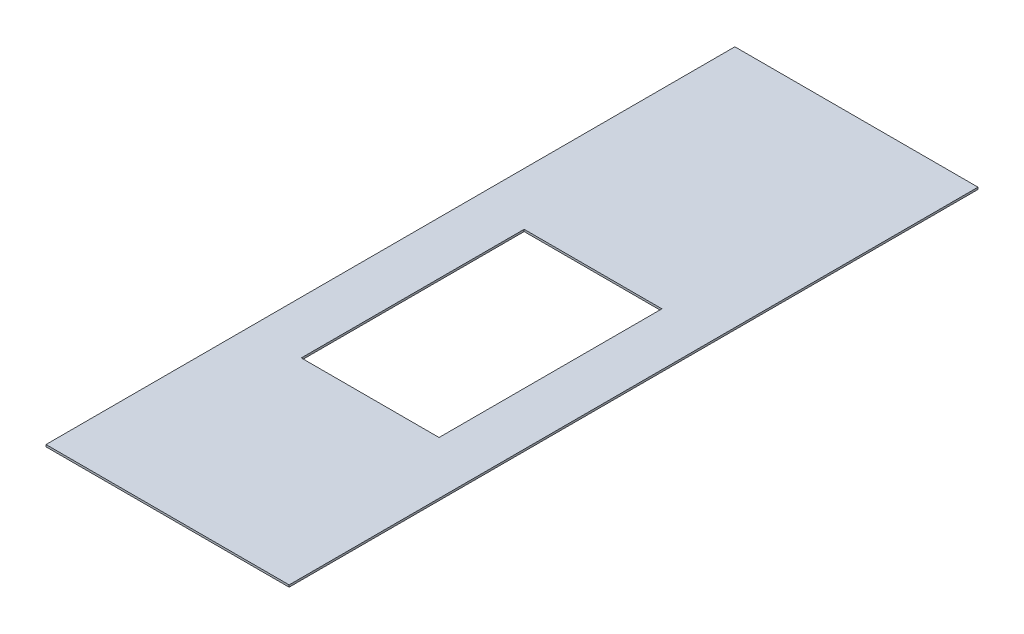
SolidWorks part; units mm, degrees
ref_plane "Front Plane" through (0, 0, 0) normal (0, 0, 1) x (1, 0, 0)
ref_plane "Top Plane" through (0, 0, 0) normal (0, 1, 0) x (1, 0, 0)
ref_plane "Right Plane" through (0, 0, 0) normal (1, 0, 0) x (0, 0, -1)
sketch "Sketch1" plane through (0, 0, 0) normal (0, 1, 0) x (1, 0, 0)
  line L1 (30, -85) -> (-30, -85)
  line L2 (30, -85) -> (30, 85)
  line L3 (30, 85) -> (-30, 85)
  line L4 (-30, -85) -> (-30, 85)
  line L5 (30, -85) -> (-30, 85) construction
  line L6 (30, 85) -> (-30, -85) construction
  point P0 (0, 0)
  dimension "D1" = 60
  dimension "D2" = 170
extrude "Boss-Extrude1" add sketch "Sketch1" along normal blind 0.5
sketch "Sketch2" plane through (0, 0, 0) normal (0, -1, 0) x (1, 0, 0)
  line L0 (30, 85) -> (30, -85) construction
  line L1 (17, -20) -> (-17, -20)
  line L2 (17, -20) -> (17, 35)
  line L3 (17, 35) -> (-17, 35)
  line L4 (-17, -20) -> (-17, 35)
  line L5 (-30, -85) -> (-30, 85) construction
  line L6 (30, -85) -> (-30, -85) construction
  line L7 (-30, 85) -> (30, 85) construction
  dimension "D1" = 13
  dimension "D2" = 13
  dimension "D3" = 65
  dimension "D4" = 50
extrude "Cut-Extrude1" cut sketch "Sketch2" against normal blind 10
